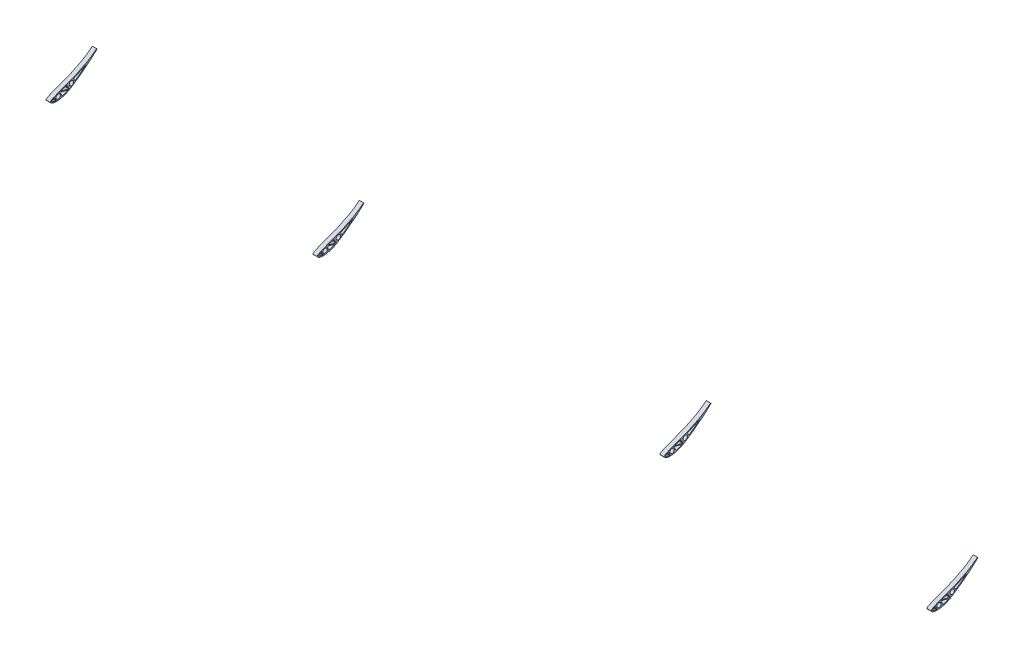
SolidWorks part; units mm, degrees
ref_plane "Front Plane" through (0, 0, 0) normal (0, 0, 1) x (1, 0, 0)
ref_plane "Top Plane" through (0, 0, 0) normal (0, 1, 0) x (1, 0, 0)
ref_plane "Right Plane" through (0, 0, 0) normal (1, 0, 0) x (0, 0, -1)
ref_plane "Plane1" through (-663.1866, 190.6859, 1129.097) normal (0, -0.8863, 0.463) x (-1, 0, 0)
sketch "Sketch2" plane through (-663.1866, 0, 0) normal (-1, 0, 0) x (0, 0, 1)
  line L0 (1168.9542, 157.0649) -> (1171.2656, 160.2017)
  line L1 (1168.5991, 157.0111) -> (1152.8543, 168.6125)
  line L2 (1153.1128, 169.0469) -> (1171.1756, 160.5791)
  line L3 (1177.8308, 151.028) -> (1181.4125, 156.8861)
  line L4 (1181.7181, 156.9915) -> (1189.5577, 154.0625)
  line L5 (1189.5319, 153.5785) -> (1178.1106, 150.6494)
  line L6 (1180.0737, 149.9801) -> (1191.1375, 152.9364)
  line L7 (1191.423, 152.5638) -> (1187.9328, 146.5284)
  line L8 (1187.6173, 146.4203) -> (1180.0436, 149.4994)
  line L9 (1199.8, 150.2493) -> (1197.4664, 144.8773)
  line L10 (1197.774, 144.5333) -> (1204.2277, 146.5168)
  line L11 (1204.3144, 146.9557) -> (1200.1943, 150.3442)
  line L13 (1129.097, 190.5217) -> (1128.8837, 191.107)
  line L14 (1128.8837, 191.107) -> (1128.8828, 191.1108)
  line L15 (1135.894, 181.267) -> (1136.6305, 182.1337) construction
  circle A1 centre (1194.2825, 148.8381) radius 3.2639
  circle A2 centre (1174.3977, 156.2245) radius 3.2639
  arc A3 (1171.2656, 160.2017) -> (1171.1756, 160.5791) centre (1171.0611, 160.3524) ccw
  arc A4 (1168.9542, 157.0649) -> (1168.5991, 157.0111) centre (1168.7498, 157.2155) cw
  arc A5 (1152.8543, 168.6125) -> (1153.1128, 169.0469) centre (1153.005, 168.817) cw
  arc A6 (1177.8308, 151.028) -> (1178.1106, 150.6494) centre (1178.0475, 150.8955) ccw
  arc A7 (1181.4125, 156.8861) -> (1181.7181, 156.9915) centre (1181.6292, 156.7536) cw
  arc A8 (1189.5577, 154.0625) -> (1189.5319, 153.5785) centre (1189.4688, 153.8245) cw
  arc A9 (1180.0737, 149.9801) -> (1180.0436, 149.4994) centre (1180.1392, 149.7347) ccw
  arc A10 (1191.423, 152.5638) -> (1191.1375, 152.9364) centre (1191.2031, 152.691) ccw
  arc A11 (1187.6173, 146.4203) -> (1187.9328, 146.5284) centre (1187.7129, 146.6556) ccw
  arc A12 (1199.8, 150.2493) -> (1200.1943, 150.3442) centre (1200.0329, 150.1481) cw
  arc A13 (1197.774, 144.5333) -> (1197.4664, 144.8773) centre (1197.6994, 144.7761) cw
  arc A14 (1204.2277, 146.5168) -> (1204.3144, 146.9557) centre (1204.153, 146.7596) ccw
  arc A15 (1136.6305, 182.1337) -> (1135.894, 181.267) centre (1136.2622, 181.7004) ccw
  spline S0 degree 3 poles (1129.0253, 190.7743) (1128.8417, 191.2007) (1129.0652, 190.7387) (1129.2798, 190.3487) (1129.8405, 189.3372) (1130.683, 188.1068) (1131.9633, 186.5546) (1133.6279, 184.8315) (1135.6529, 182.95) (1138.0106, 180.9614) (1140.6791, 178.8994) (1143.6274, 176.797) (1146.825, 174.6871) (1150.2335, 172.5953) (1153.8144, 170.5466) (1157.5274, 168.5631) (1161.3292, 166.6608) (1165.1761, 164.8534) (1169.0269, 163.1538) (1172.8369, 161.5643) (1176.5667, 160.0898) (1180.1759, 158.7288) (1183.6283, 157.4779) (1186.8888, 156.3294) (1189.9259, 155.2712) (1192.7185, 154.2977) (1195.2474, 153.3469) (1197.5173, 152.4005) (1199.555, 151.5079) (1201.354, 150.6789) (1202.8946, 149.9201) (1204.1688, 149.2554) (1205.1372, 148.6495) (1205.8391, 148.1961) (1206.2288, 147.6298) (1206.0758, 147.0312) (1205.7758, 146.4554) (1205.265, 145.8648) (1204.5826, 145.2995) (1203.7285, 144.7823) (1202.7149, 144.3291) (1201.5329, 143.977) (1200.1899, 143.7308) (1198.694, 143.5746) (1197.0551, 143.5244) (1195.2865, 143.5858) (1193.4005, 143.7629) (1191.4097, 144.0667) (1189.3263, 144.4949) (1187.1654, 145.0568) (1184.9404, 145.7568) (1182.6673, 146.6182) (1180.345, 147.6404) (1177.9774, 148.8506) (1175.5583, 150.2399) (1173.0657, 151.7602) (1170.52, 153.4166) (1167.9265, 155.1848) (1165.2946, 157.0449) (1162.6354, 158.9714) (1159.9688, 160.9456) (1157.3137, 162.9454) (1154.6945, 164.9603) (1152.1309, 166.9772) (1149.639, 168.9824) (1147.237, 170.9667) (1144.9369, 172.9154) (1142.7546, 174.8185) (1140.7009, 176.6617) (1138.7886, 178.4344) (1137.0291, 180.1256) (1135.4321, 181.7251) (1134.0053, 183.2222) (1132.7568, 184.6088) (1131.6923, 185.8761) (1130.816, 187.0169) (1130.1258, 188.0237) (1129.6308, 188.9371) (1129.3397, 189.7276) (1129.118, 190.4407) (1129.0253, 190.7743) (1128.8417, 191.2007) (1129.0652, 190.7387) knots -0.007483 -0.003649 -0.00098 0 0.001 0.004147 0.009748 0.018044 0.028864 0.041831 0.056714 0.073341 0.091508 0.111022 0.131662 0.153208 0.175433 0.19811 0.221011 0.243906 0.266573 0.28881 0.310405 0.331178 0.350944 0.369556 0.386865 0.402753 0.417196 0.43038 0.442363 0.453032 0.462284 0.470026 0.476177 0.48065 0.483553 0.486421 0.489953 0.494097 0.498851 0.504197 0.510125 0.516691 0.524012 0.532092 0.540898 0.550403 0.560581 0.571396 0.582828 0.59483 0.607347 0.620384 0.633969 0.6482 0.663194 0.678899 0.695227 0.712113 0.729459 0.747143 0.76501 0.782905 0.800688 0.818242 0.835449 0.852212 0.86843 0.884009 0.898855 0.912882 0.926011 0.938167 0.94929 0.959322 0.968217 0.975948 0.982474 0.987905 0.992517 0.996351 0.99902 1 1.001 1.004147 1.009748 only from (1128.8828, 191.1108) to (1129.097, 190.5217) construction
  spline S1 degree 3 poles (1136.6305, 182.1337) (1137.0661, 181.7635) (1138.3751, 180.6797) (1140.6791, 178.8994) (1143.6274, 176.797) (1146.825, 174.6871) (1150.2335, 172.5953) (1153.8144, 170.5466) (1157.5274, 168.5631) (1161.3292, 166.6608) (1165.1761, 164.8534) (1169.0269, 163.1538) (1172.8369, 161.5643) (1176.5667, 160.0898) (1180.1759, 158.7288) (1183.6283, 157.4779) (1186.8888, 156.3294) (1189.9259, 155.2712) (1192.7185, 154.2977) (1195.2474, 153.3469) (1197.5173, 152.4005) (1199.555, 151.5079) (1201.354, 150.6789) (1202.8946, 149.9201) (1204.1688, 149.2554) (1205.1372, 148.6495) (1205.8391, 148.1961) (1206.2288, 147.6298) (1206.0758, 147.0312) (1205.7758, 146.4554) (1205.265, 145.8648) (1204.5826, 145.2995) (1203.7285, 144.7823) (1202.7149, 144.3291) (1201.5329, 143.977) (1200.1899, 143.7308) (1198.694, 143.5746) (1197.0551, 143.5244) (1195.2865, 143.5858) (1193.4005, 143.7629) (1191.4097, 144.0667) (1189.3263, 144.4949) (1187.1654, 145.0568) (1184.9404, 145.7568) (1182.6673, 146.6182) (1180.345, 147.6404) (1177.9774, 148.8506) (1175.5583, 150.2399) (1173.0657, 151.7602) (1170.52, 153.4166) (1167.9265, 155.1848) (1165.2946, 157.0449) (1162.6354, 158.9714) (1159.9688, 160.9456) (1157.3137, 162.9454) (1154.6945, 164.9603) (1152.1309, 166.9772) (1149.639, 168.9824) (1147.237, 170.9667) (1144.9369, 172.9154) (1142.7546, 174.8185) (1140.7009, 176.6617) (1138.7886, 178.4344) (1137.1771, 179.9834) (1136.2105, 180.9463) (1135.8245, 181.3373) knots 0.064133 0.064133 0.064133 0.064133 0.073341 0.091508 0.111022 0.131662 0.153208 0.175433 0.19811 0.221011 0.243906 0.266573 0.28881 0.310405 0.331178 0.350944 0.369556 0.386865 0.402753 0.417196 0.43038 0.442363 0.453032 0.462284 0.470026 0.476177 0.48065 0.483553 0.486421 0.489953 0.494097 0.498851 0.504197 0.510125 0.516691 0.524012 0.532092 0.540898 0.550403 0.560581 0.571396 0.582828 0.59483 0.607347 0.620384 0.633969 0.6482 0.663194 0.678899 0.695227 0.712113 0.729459 0.747143 0.76501 0.782905 0.800688 0.818242 0.835449 0.852212 0.86843 0.884009 0.898855 0.912882 0.926011 0.93486 0.93486 0.93486 0.93486
  spline S2 degree 3 poles (1129.097, 190.5217) (1129.0617, 190.642) (1129.0125, 190.8041) (1128.8417, 191.2007) (1128.9861, 190.9022) (1129.0595, 190.7578) (1129.097, 190.6859) knots 0.996676 0.996676 0.996676 0.996676 0.99902 1 1.001 1.002333 1.002333 1.002333 1.002333 construction
  dimension "D1" = 0.254
  dimension "D2" = 0.254
  dimension "D3" = 0.254
  dimension "D4" = 0.254
  dimension "D5" = 0.254
  dimension "D6" = 0.254
  dimension "D7" = 0.254
  dimension "D8" = 0.254
  dimension "D9" = 0.254
  dimension "D10" = 0.254
  dimension "D11" = 0.254
  dimension "D12" = 0.254
  dimension "D13" = 6.5278
extrude "Boss-Extrude1" add sketch "Sketch2" against normal blind 6.35
ref_plane "Plane2" through (-459.9866, 0, 0) normal (1, 0, 0) x (0, 0, -1)
mirror "Mirror1" about plane through (-459.9866, 0, 0) normal (1, 0, 0) of bodies 101
ref_plane "Plane4" through (-2.54, 0, 0) normal (-1, 0, 0) x (0, 0, 1)
ref_plane "Plane5" through (0, 0, 0) normal (1, 0, 0) x (0, 0, -1)
mirror "Mirror3" about plane through (0, 0, 0) normal (1, 0, 0) of bodies 102
ref_plane "Plane6" through (459.9866, 0, 0) normal (1, 0, 0) x (0, 0, -1)
mirror "Mirror4" about plane through (459.9866, 0, 0) normal (1, 0, 0) of bodies 104
